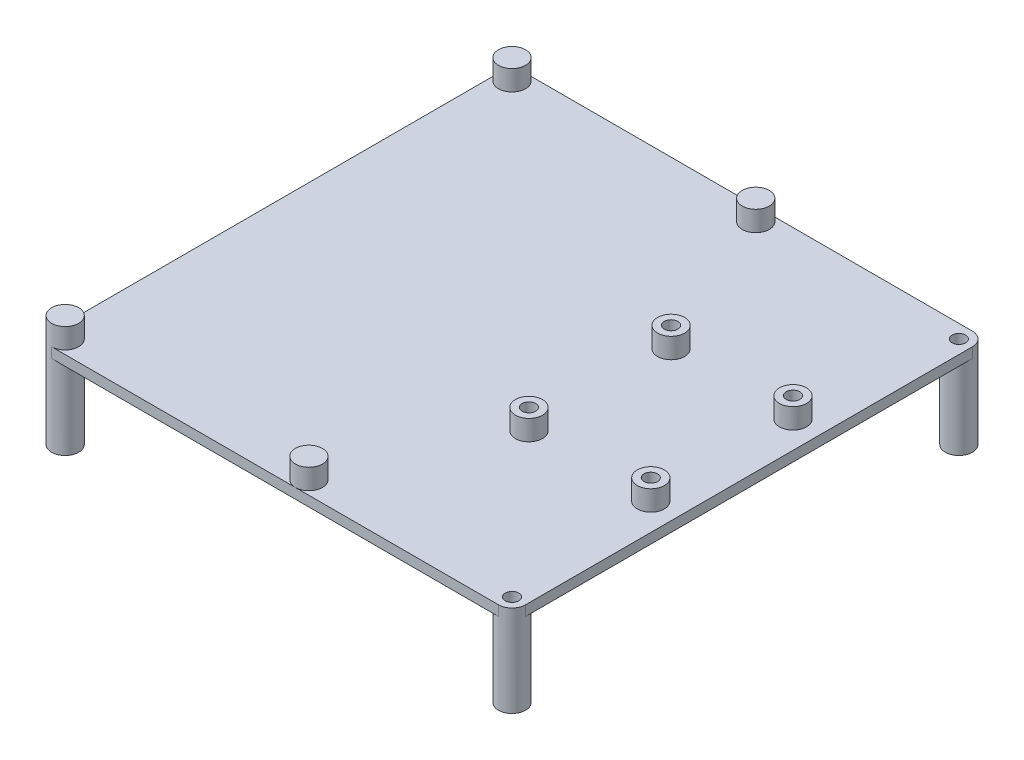
SolidWorks part; units mm, degrees
ref_plane "Front Plane" through (0, 0, 0) normal (0, 0, 1) x (1, 0, 0)
ref_plane "Top Plane" through (0, 0, 0) normal (0, 1, 0) x (1, 0, 0)
ref_plane "Right Plane" through (0, 0, 0) normal (1, 0, 0) x (0, 0, -1)
sketch "Sketch1" plane through (0, 0, 0) normal (0, 1, 0) x (1, 0, 0)
  line L0 (0, 0) -> (0, 16.9463) construction
  line L1 (-35, -35) -> (35, -35)
  line L2 (-35, -35) -> (-35, 35)
  line L3 (-35, 35) -> (35, 35)
  line L4 (35, -35) -> (35, 35)
  line L5 (-35, -35) -> (35, 35) construction
  line L6 (-35, 35) -> (35, -35) construction
  line L7 (0, 0) -> (11.0825, 0) construction
  circle A0 centre (-33, 33) radius 1
  circle A1 centre (-33, -33) radius 1
  circle A2 centre (33, -33) radius 1
  circle A3 centre (33, 33) radius 1
  point P0 (0, 0)
  dimension "D3" = 2
  dimension "D1" = 70
  dimension "D2" = 70
  dimension "D4" = 2
extrude "Boss-Extrude1" add sketch "Sketch1" along normal blind 1.5
fillet "Fillet1" radius 2 4 edges at (-35, 0.75, -35) (35, 0.75, -35) (35, 0.75, 35) (-35, 0.75, 35)
sketch "Sketch2" plane through (0, 0, 0) normal (0, -1, 0) x (1, 0, 0)
  line L0 (0, 0) -> (0, -22) construction
  line L1 (-7.25, -30.25) -> (7.25, -30.25)
  line L2 (-7.25, -30.25) -> (-7.25, -13.75)
  line L3 (-7.25, -13.75) -> (7.25, -13.75)
  line L4 (7.25, -30.25) -> (7.25, -13.75)
  line L5 (-7.25, -30.25) -> (7.25, -13.75) construction
  line L6 (-7.25, -13.75) -> (7.25, -30.25) construction
  point P0 (0, -22)
  dimension "D1" = 14.5
  dimension "D2" = 16.5
  dimension "D3" = 22
extrude "Cut-Extrude3" cut sketch "Sketch2" against normal blind 0.1
sketch "Sketch3" plane through (0, 0, 0) normal (0, -1, 0) x (1, 0, 0)
  line L0 (0, 0) -> (0, 5) construction
  line L1 (0, 5) -> (7, 5) construction
  circle A0 centre (7, 5) radius 2
  circle A1 centre (7, 5) radius 3
  circle A2 centre (-7, 5) radius 2
  circle A3 centre (-7, 5) radius 3
  dimension "D1" = 4
  dimension "D2" = 6
  dimension "D3" = 7
  dimension "D4" = 5
extrude "Boss-Extrude2" add sketch "Sketch3" along normal blind 3
sketch "Sketch4" plane through (0, 1.5, 0) normal (0, 1, 0) x (1, 0, 0)
  line L0 (-35, 33) -> (-35, -33) construction
  line L1 (5, -35) -> (-35, -35)
  line L2 (5, -35) -> (5, 35)
  line L3 (5, 35) -> (-35, 35)
  line L4 (-35, -35) -> (-35, 35)
  line L5 (5, -35) -> (-35, 35) construction
  line L6 (5, 35) -> (-35, -35) construction
  line L7 (-33, -35) -> (33, -35) construction
  line L8 (33, 35) -> (-33, 35) construction
  line L9 (0, 0) -> (13.68, 0) construction
  circle A0 centre (3, 33) radius 2
  circle A1 centre (-33, 33) radius 1 construction
  circle A2 centre (3, -33) radius 2
  circle A3 centre (-33, 33) radius 2
  circle A4 centre (-33, -33) radius 2
  point P0 (-15, 0)
  arc M8 (-33, 35) -> (-35, 33) centre (-33, 33) ccw
  arc M10 (-35, -33) -> (-33, -35) centre (-33, -33) ccw
  circle M15 centre (-33, 33) radius 1
  circle M16 centre (-33, -33) radius 1
  dimension "D2" = 36
  dimension "D3" = 4
  dimension "D5" = 4
  dimension "D6" = 4
  dimension "D1" = 40
  dimension "D4" = 66
extrude "Boss-Extrude3" add sketch "Sketch4" along normal blind 3 contours A4 M10 M16 | M16 | A2 | A0 | A3 M8 M15 | M15
sketch "Sketch5" plane through (0, 1.5, 0) normal (0, 1, 0) x (1, 0, 0)
  line L0 (0, 0) -> (22, 0) construction
  line L1 (31, -10.5) -> (13, -10.5) construction
  line L2 (31, -10.5) -> (31, 10.5) construction
  line L3 (31, 10.5) -> (13, 10.5) construction
  line L4 (13, -10.5) -> (13, 10.5) construction
  line L5 (31, -10.5) -> (13, 10.5) construction
  line L6 (31, 10.5) -> (13, -10.5) construction
  circle A0 centre (13, 10.5) radius 2
  circle A1 centre (31, 10.5) radius 2
  circle A2 centre (31, -10.5) radius 2
  circle A3 centre (13, -10.5) radius 2
  circle A4 centre (13, -10.5) radius 1
  circle A5 centre (13, 10.5) radius 1
  circle A6 centre (31, 10.5) radius 1
  circle A7 centre (31, -10.5) radius 1
  point P0 (22, 0)
  dimension "D3" = 2
  dimension "D4" = 4
  dimension "D5" = 22
  dimension "D1" = 18
  dimension "D2" = 21
extrude "Boss-Extrude4" add sketch "Sketch5" along normal blind 3
sketch "Sketch6" plane through (0, 0, 0) normal (0, -1, 0) x (1, 0, 0)
  circle A0 centre (-33, 33) radius 2
  arc A1 (-33, 35) -> (-35, 33) centre (-33, 33) ccw construction
  circle A2 centre (33, 33) radius 2
  circle A3 centre (33, -33) radius 2
  circle A4 centre (-33, -33) radius 2
  arc A5 (-35, -33) -> (-33, -35) centre (-33, -33) ccw construction
  arc A6 (33, -35) -> (35, -33) centre (33, -33) ccw construction
  arc A7 (35, 33) -> (33, 35) centre (33, 33) ccw construction
  circle A8 centre (-33, -33) radius 1 construction
  circle A9 centre (33, -33) radius 1 construction
  circle A10 centre (33, 33) radius 1 construction
  circle A11 centre (-33, 33) radius 1 construction
  circle A12 centre (-33, -33) radius 1
  circle A13 centre (33, -33) radius 1
  circle A14 centre (33, 33) radius 1
  circle A15 centre (-33, 33) radius 1
extrude "Boss-Extrude5" add sketch "Sketch6" along normal blind 12
